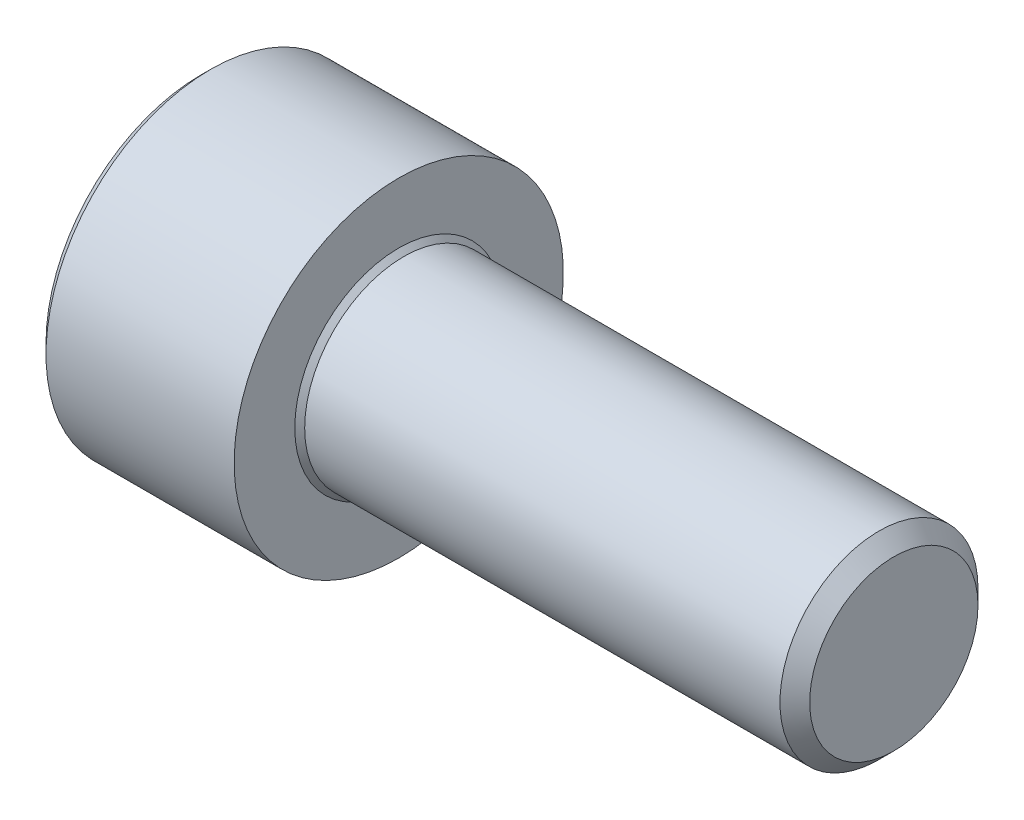
SolidWorks part; units mm, degrees
material "Galvanized Steel"
ref_plane "Front Plane" through (0, 0, 0) normal (0, 0, 1) x (1, 0, 0)
ref_plane "Top Plane" through (0, 0, 0) normal (0, 1, 0) x (1, 0, 0)
ref_plane "Right Plane" through (0, 0, 0) normal (1, 0, 0) x (0, 0, -1)
sketch "Sketch2" plane through (0, 0, 0) normal (1, 0, 0) x (0, 0, -1)
  circle A0 centre (0, 0) radius 4
  dimension "D1" = 8
extrude "Boss-Extrude1" add sketch "Sketch2" against normal blind 20
chamfer "Chamfer1" distance 0.6 angle 45 1 edges at (0, 0, -4)
sketch "Sketch6" plane through (0, 0, 0) normal (0, 0, 1) x (1, 0, 0)
  line L0 (-28, 0) -> (-28, 6.65)
  line L1 (-28, 0) -> (-20, 0)
  line L2 (-28, 6.65) -> (-20, 6.65)
  line L6 (-20, 6.65) -> (-20, 0)
  line L8 (-20, 0) -> (-14.6471, 0) construction
  line L10 (-20, 4) -> (-20, -4) construction
  dimension "D1" = 8
  dimension "D2" = 13.3
revolve "Revolve1" add sketch "Sketch6" angle 360 about L8
sketch "Sketch7" plane through (-28, 0, 0) normal (-1, 0, 0) x (0, 0, 1)
  line L1 (0, 3.5796) -> (-3.1, 1.7898)
  line L2 (-3.1, 1.7898) -> (-3.1, -1.7898)
  line L3 (-3.1, -1.7898) -> (0, -3.5796)
  line L4 (0, -3.5796) -> (3.1, -1.7898)
  line L5 (3.1, -1.7898) -> (3.1, 1.7898)
  line L6 (3.1, 1.7898) -> (0, 3.5796)
  circle A0 centre (0, 0) radius 3.1 construction
  dimension "D1" = 6.2
extrude "Cut-Extrude1" cut sketch "Sketch7" against normal blind 4
sketch "Sketch8" plane through (-28, 0, 0) normal (-1, 0, 0) x (0, 0, 1)
  circle A0 centre (0, 0) radius 3.6296
  dimension "D1" = 0.05
extrude "Cut-Extrude2" cut sketch "Sketch8" against normal blind 1 draft 45
chamfer "Chamfer2" distance 0.4 angle 45 1 edges at (-28, -6.65, 0)
chamfer "Chamfer3" distance 0.2 angle 45 1 edges at (-20, -4, 0)
